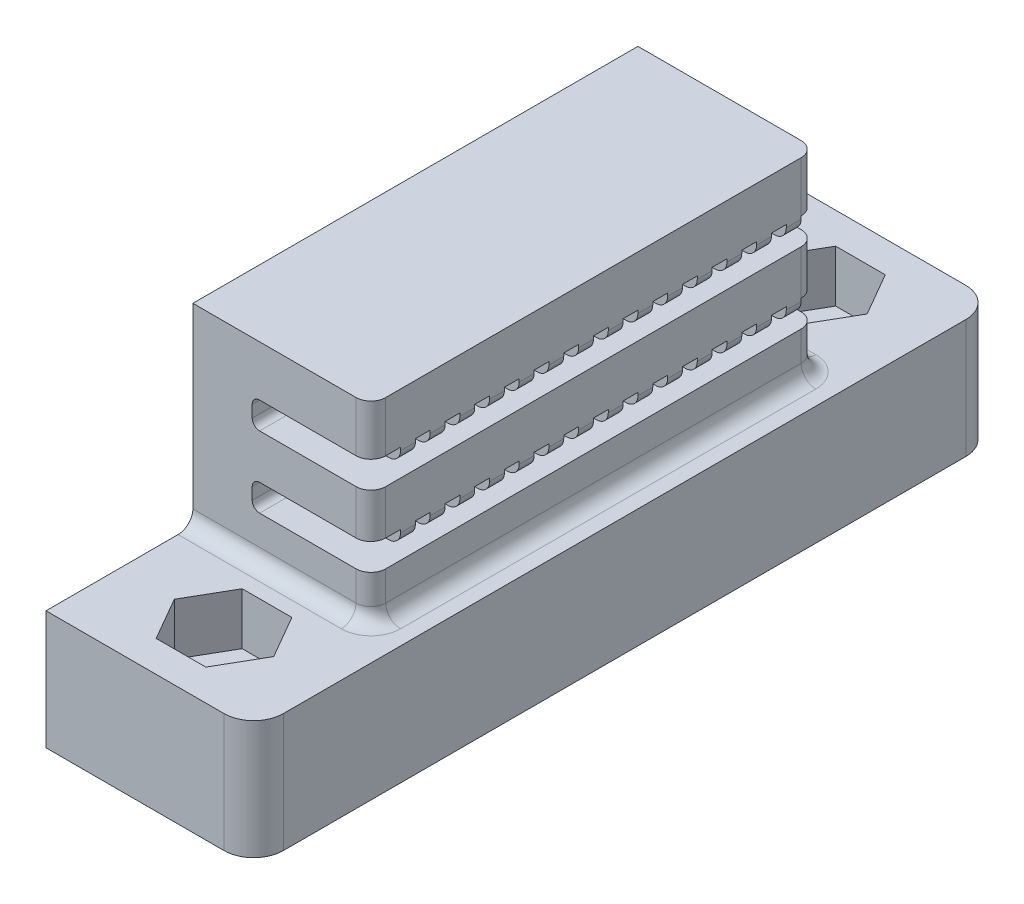
SolidWorks part; units mm, degrees
ref_plane "Alzado" through (0, 0, 0) normal (0, 0, 1) x (1, 0, 0)
ref_plane "Planta" through (0, 0, 0) normal (0, 1, 0) x (1, 0, 0)
ref_plane "Vista lateral" through (0, 0, 0) normal (1, 0, 0) x (0, 0, -1)
sketch "Croquis1" plane through (0, 0, 0) normal (0, 1, 0) x (1, 0, 0)
  line L0 (0, 25) -> (14, 25) construction
  line L1 (0, 0) -> (14, 0)
  line L2 (0, 0) -> (0, 50)
  line L3 (0, 50) -> (14, 50)
  line L4 (14, 0) -> (14, 50)
  line L5 (7, 50) -> (7, 0) construction
  circle A0 centre (7, 45) radius 1.55
  circle A1 centre (7, 5) radius 1.55
  dimension "D3" = 3.1
  dimension "D1" = 50
  dimension "D2" = 14
  dimension "D4" = 20
extrude "Saliente-Extruir1" add sketch "Croquis1" along normal blind 8
sketch "Croquis2" plane through (0, 8, 0) normal (0, 1, 0) x (1, 0, 0)
  line L1 (10.3486, 45) -> (8.6743, 47.9)
  line L2 (8.6743, 47.9) -> (5.3257, 47.9)
  line L3 (5.3257, 47.9) -> (3.6514, 45)
  line L4 (3.6514, 45) -> (5.3257, 42.1)
  line L5 (5.3257, 42.1) -> (8.6743, 42.1)
  line L6 (8.6743, 42.1) -> (10.3486, 45)
  line L7 (10.3486, 5) -> (8.6743, 7.9)
  line L8 (8.6743, 7.9) -> (5.3257, 7.9)
  line L9 (5.3257, 7.9) -> (3.6514, 5)
  line L10 (3.6514, 5) -> (5.3257, 2.1)
  line L11 (5.3257, 2.1) -> (8.6743, 2.1)
  line L12 (8.6743, 2.1) -> (10.3486, 5)
  circle A2 centre (7, 45) radius 2.9 construction
  circle A3 centre (7, 5) radius 2.9 construction
  dimension "D1" = 5.8
  dimension "D2" = 5.8
extrude "Cortar-Extruir1" cut sketch "Croquis2" against normal blind 3.5
sketch "Croquis3" plane through (0, 8, 0) normal (0, 1, 0) x (1, 0, 0)
  line L0 (0, 50) -> (0, 0) construction
  line L1 (0, 39.9) -> (14, 39.9)
  line L2 (0, 39.9) -> (0, 9.9)
  line L3 (0, 9.9) -> (14, 9.9)
  line L4 (14, 39.9) -> (14, 9.9)
  line L5 (14, 0) -> (14, 50) construction
  line L6 (5.3257, 42.1) -> (8.6743, 42.1) construction
  dimension "D1" = 30
  dimension "D2" = 2.2
extrude "Saliente-Extruir3" add sketch "Croquis3" along normal blind 13
sketch "Croquis4" plane through (14, 0, 0) normal (1, 0, 0) x (0, 0, -1)
  line L0 (39.9, 21) -> (39.9, 8) construction
  line L1 (39.9, 17.6) -> (38.9, 17.6)
  line L2 (39.9, 17.6) -> (39.9, 15.8)
  line L3 (39.9, 15.8) -> (9.9, 15.8)
  line L4 (9.9, 17.6) -> (9.9, 15.8)
  line L5 (9.9, 21) -> (9.9, 8) construction
  line L6 (39.9, 8) -> (50, 8) construction
  line L7 (39.9, 12.8) -> (38.9, 12.8)
  line L8 (39.9, 12.8) -> (39.9, 11)
  line L9 (39.9, 11) -> (9.9, 11)
  line L10 (9.9, 12.8) -> (9.9, 11)
  line L11 (36.9, 17.6) -> (36.9, 16.6)
  line L13 (38.9, 17.6) -> (38.9, 16.6)
  line L14 (38.9, 16.6) -> (37.9, 16.6)
  line L15 (37.9, 17.6) -> (37.9, 16.6)
  line L16 (36.9, 16.6) -> (35.9, 16.6)
  line L17 (35.9, 17.6) -> (35.9, 16.6)
  line L18 (34.9, 17.6) -> (34.9, 16.6)
  line L19 (34.9, 16.6) -> (33.9, 16.6)
  line L20 (33.9, 17.6) -> (33.9, 16.6)
  line L21 (32.9, 17.6) -> (32.9, 16.6)
  line L22 (32.9, 16.6) -> (31.9, 16.6)
  line L23 (31.9, 17.6) -> (31.9, 16.6)
  line L24 (30.9, 17.6) -> (30.9, 16.6)
  line L25 (30.9, 16.6) -> (29.9, 16.6)
  line L26 (29.9, 17.6) -> (29.9, 16.6)
  line L27 (28.9, 17.6) -> (28.9, 16.6)
  line L28 (28.9, 16.6) -> (27.9, 16.6)
  line L29 (27.9, 17.6) -> (27.9, 16.6)
  line L30 (26.9, 17.6) -> (26.9, 16.6)
  line L31 (26.9, 16.6) -> (25.9, 16.6)
  line L32 (25.9, 17.6) -> (25.9, 16.6)
  line L33 (24.9, 17.6) -> (24.9, 16.6)
  line L34 (24.9, 16.6) -> (23.9, 16.6)
  line L35 (23.9, 17.6) -> (23.9, 16.6)
  line L36 (22.9, 17.6) -> (22.9, 16.6)
  line L37 (22.9, 16.6) -> (21.9, 16.6)
  line L38 (21.9, 17.6) -> (21.9, 16.6)
  line L39 (20.9, 17.6) -> (20.9, 16.6)
  line L40 (20.9, 16.6) -> (19.9, 16.6)
  line L41 (19.9, 17.6) -> (19.9, 16.6)
  line L42 (18.9, 17.6) -> (18.9, 16.6)
  line L43 (18.9, 16.6) -> (17.9, 16.6)
  line L44 (17.9, 17.6) -> (17.9, 16.6)
  line L45 (16.9, 17.6) -> (16.9, 16.6)
  line L46 (16.9, 16.6) -> (15.9, 16.6)
  line L47 (15.9, 17.6) -> (15.9, 16.6)
  line L48 (14.9, 17.6) -> (14.9, 16.6)
  line L49 (14.9, 16.6) -> (13.9, 16.6)
  line L50 (13.9, 17.6) -> (13.9, 16.6)
  line L51 (12.9, 17.6) -> (12.9, 16.6)
  line L52 (12.9, 16.6) -> (11.9, 16.6)
  line L53 (11.9, 17.6) -> (11.9, 16.6)
  line L54 (38.9, 17.6) -> (36.9, 17.6) construction
  line L55 (36.9, 12.8) -> (36.9, 11.8)
  line L57 (38.9, 12.8) -> (38.9, 11.8)
  line L58 (38.9, 11.8) -> (37.9, 11.8)
  line L59 (37.9, 12.8) -> (37.9, 11.8)
  line L60 (36.9, 11.8) -> (35.9, 11.8)
  line L61 (35.9, 12.8) -> (35.9, 11.8)
  line L62 (34.9, 12.8) -> (34.9, 11.8)
  line L63 (34.9, 11.8) -> (33.9, 11.8)
  line L64 (33.9, 12.8) -> (33.9, 11.8)
  line L65 (32.9, 12.8) -> (32.9, 11.8)
  line L66 (32.9, 11.8) -> (31.9, 11.8)
  line L67 (31.9, 12.8) -> (31.9, 11.8)
  line L68 (30.9, 12.8) -> (30.9, 11.8)
  line L69 (30.9, 11.8) -> (29.9, 11.8)
  line L70 (29.9, 12.8) -> (29.9, 11.8)
  line L71 (28.9, 12.8) -> (28.9, 11.8)
  line L72 (28.9, 11.8) -> (27.9, 11.8)
  line L73 (27.9, 12.8) -> (27.9, 11.8)
  line L74 (26.9, 12.8) -> (26.9, 11.8)
  line L75 (26.9, 11.8) -> (25.9, 11.8)
  line L76 (25.9, 12.8) -> (25.9, 11.8)
  line L77 (24.9, 12.8) -> (24.9, 11.8)
  line L78 (24.9, 11.8) -> (23.9, 11.8)
  line L79 (23.9, 12.8) -> (23.9, 11.8)
  line L80 (22.9, 12.8) -> (22.9, 11.8)
  line L81 (22.9, 11.8) -> (21.9, 11.8)
  line L82 (21.9, 12.8) -> (21.9, 11.8)
  line L83 (20.9, 12.8) -> (20.9, 11.8)
  line L84 (20.9, 11.8) -> (19.9, 11.8)
  line L85 (19.9, 12.8) -> (19.9, 11.8)
  line L86 (18.9, 12.8) -> (18.9, 11.8)
  line L87 (18.9, 11.8) -> (17.9, 11.8)
  line L88 (17.9, 12.8) -> (17.9, 11.8)
  line L89 (16.9, 12.8) -> (16.9, 11.8)
  line L90 (16.9, 11.8) -> (15.9, 11.8)
  line L91 (15.9, 12.8) -> (15.9, 11.8)
  line L92 (14.9, 12.8) -> (14.9, 11.8)
  line L93 (14.9, 11.8) -> (13.9, 11.8)
  line L94 (13.9, 12.8) -> (13.9, 11.8)
  line L95 (12.9, 12.8) -> (12.9, 11.8)
  line L96 (12.9, 11.8) -> (11.9, 11.8)
  line L97 (11.9, 12.8) -> (11.9, 11.8)
  line L98 (38.9, 12.8) -> (36.9, 12.8) construction
  line L99 (37.9, 17.6) -> (36.9, 17.6)
  line L100 (35.9, 17.6) -> (34.9, 17.6)
  line L101 (33.9, 17.6) -> (32.9, 17.6)
  line L102 (31.9, 17.6) -> (30.9, 17.6)
  line L103 (29.9, 17.6) -> (28.9, 17.6)
  line L104 (27.9, 17.6) -> (26.9, 17.6)
  line L105 (25.9, 17.6) -> (24.9, 17.6)
  line L106 (23.9, 17.6) -> (22.9, 17.6)
  line L107 (21.9, 17.6) -> (20.9, 17.6)
  line L108 (19.9, 17.6) -> (18.9, 17.6)
  line L109 (17.9, 17.6) -> (16.9, 17.6)
  line L110 (15.9, 17.6) -> (14.9, 17.6)
  line L111 (13.9, 17.6) -> (12.9, 17.6)
  line L112 (11.9, 17.6) -> (9.9, 17.6)
  line L113 (37.9, 12.8) -> (36.9, 12.8)
  line L114 (35.9, 12.8) -> (34.9, 12.8)
  line L115 (33.9, 12.8) -> (32.9, 12.8)
  line L116 (31.9, 12.8) -> (30.9, 12.8)
  line L117 (29.9, 12.8) -> (28.9, 12.8)
  line L118 (27.9, 12.8) -> (26.9, 12.8)
  line L119 (25.9, 12.8) -> (24.9, 12.8)
  line L120 (23.9, 12.8) -> (22.9, 12.8)
  line L121 (21.9, 12.8) -> (20.9, 12.8)
  line L122 (19.9, 12.8) -> (18.9, 12.8)
  line L123 (17.9, 12.8) -> (16.9, 12.8)
  line L124 (15.9, 12.8) -> (14.9, 12.8)
  line L125 (13.9, 12.8) -> (12.9, 12.8)
  line L126 (11.9, 12.8) -> (9.9, 12.8)
  dimension "D1" = 1.8
  dimension "D2" = 1.8
  dimension "D3" = 3
  dimension "D4" = 3
  dimension "D5" = 1
  dimension "D6" = 1
  dimension "D7" = 1
  dimension "D9" = 2
  dimension "D10" = 1
  dimension "D11" = 1
  dimension "D12" = 1
  dimension "D14" = 2
  dimension "D8" = 14
  dimension "D13" = 14
extrude "Cortar-Extruir2" cut sketch "Croquis4" against normal blind 10
sketch "Croquis5" plane through (14, 0, 0) normal (1, 0, 0) x (0, 0, -1)
  line L1 (39.9, 8) -> (9.9, 8)
  line L2 (39.9, 8) -> (39.9, 21)
  line L3 (39.9, 21) -> (9.9, 21)
  line L4 (9.9, 8) -> (9.9, 21)
extrude "Cortar-Extruir3" cut sketch "Croquis5" against normal blind 2
fillet "Redondeo1" radius 0.8 28 edges at (12, 11.8, -12.4) (12, 11.8, -14.4) (12, 11.8, -16.4) (12, 11.8, -18.4) (12, 11.8, -20.4) (12, 11.8, -22.4) (12, 11.8, -24.4) (12, 11.8, -26.4) (12, 11.8, -28.4) (12, 11.8, -30.4) (12, 11.8, -32.4) (12, 11.8, -34.4) (12, 11.8, -36.4) (12, 11.8, -38.4) (12, 16.6, -38.4) (12, 16.6, -36.4) (12, 16.6, -34.4) (12, 16.6, -32.4) (12, 16.6, -30.4) (12, 16.6, -28.4) (12, 16.6, -26.4) (12, 16.6, -24.4) (12, 16.6, -22.4) (12, 16.6, -20.4) (12, 16.6, -18.4) (12, 16.6, -16.4) (12, 16.6, -14.4) (12, 16.6, -12.4)
fillet "Redondeo2" radius 2 2 edges at (14, 4, -50) (14, 4, 0)
fillet "Redondeo3" radius 1 6 edges at (12, 19.3, -39.9) (12, 14.3, -39.9) (12, 9.5, -39.9) (12, 9.5, -9.9) (12, 14.3, -9.9) (12, 19.3, -9.9)
fillet "Redondeo4" radius 1 5 edges at (5.5, 8, -9.9) (11.7071, 8, -10.1929) (12, 8, -24.9) (11.7071, 8, -39.6071) (5.5, 8, -39.9)
fillet "Redondeo5" radius 0.5 32 edges at (4, 12.8, -10.9) (4, 12.8, -13.4) (4, 12.8, -15.4) (4, 12.8, -17.4) (4, 12.8, -19.4) (4, 12.8, -21.4) (4, 12.8, -25.4) (4, 12.8, -23.4) (4, 12.8, -27.4) (4, 12.8, -29.4) (4, 12.8, -31.4) (4, 12.8, -33.4) (4, 12.8, -35.4) (4, 12.8, -37.4) (4, 12.8, -39.4) (4, 17.6, -39.4) (4, 17.6, -37.4) (4, 17.6, -35.4) (4, 17.6, -33.4) (4, 17.6, -31.4) (4, 17.6, -29.4) (4, 17.6, -27.4) (4, 17.6, -25.4) (4, 17.6, -23.4) (4, 17.6, -21.4) (4, 17.6, -19.4) (4, 17.6, -17.4) (4, 17.6, -15.4) (4, 17.6, -13.4) (4, 17.6, -10.9) (4, 15.8, -24.9) (4, 11, -24.9)
